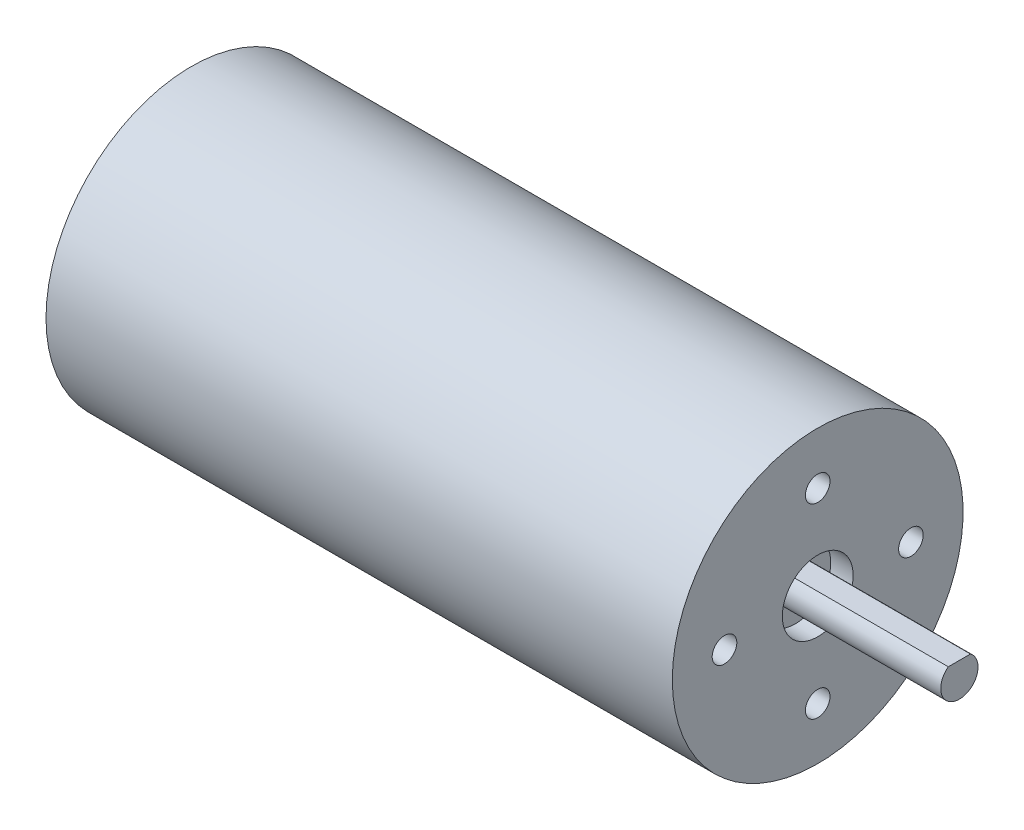
SolidWorks part; units mm, degrees
ref_plane "Front Plane" through (0, 0, 0) normal (0, 0, 1) x (1, 0, 0)
ref_plane "Top Plane" through (0, 0, 0) normal (0, 1, 0) x (1, 0, 0)
ref_plane "Right Plane" through (0, 0, 0) normal (1, 0, 0) x (0, 0, -1)
sketch "Sketch1" plane through (0, 0, 0) normal (1, 0, 0) x (0, 0, -1)
  circle A0 centre (0, 0) radius 19.5
  dimension "D1" = 39
extrude "Boss-Extrude1" add sketch "Sketch1" along normal mid plane 84
sketch "Sketch2" plane through (42, 0, 0) normal (1, 0, 0) x (0, 0, -1)
  circle A0 centre (0, 0) radius 4.75
  dimension "D1" = 9.5
extrude "Cut-Extrude1" cut sketch "Sketch2" against normal blind 3
sketch "Sketch3" plane through (39, 0, 0) normal (1, 0, 0) x (0, 0, -1)
  line L0 (-1.4866, 2.01) -> (1.4866, 2.01)
  arc A0 (-1.4866, 2.01) -> (1.4866, 2.01) centre (0, 0) ccw
  dimension "D1" = 5
  dimension "D2" = 2.01
extrude "Boss-Extrude2" add sketch "Sketch3" along normal blind 22
hole_wizard "Tap Drill for M4x0.7 Tap1" positions "Sketch5" profile "Sketch4" hole size "M4x0.7" standard "ANSI Metric"
sketch "Sketch5" plane through (42, 0, 0) normal (1, 0, 0) x (0, 0, -1)
  line L1 (0, 12.5) -> (0, -12.5) construction
  point P0 (0, 12.5)
  point P11 (12.5, 0)
  point P12 (0, -12.5)
  point P13 (-12.5, 0)
  dimension "D1" = 25
  dimension "D2" = 4
sketch "Sketch4" plane through (42, 12.5, 0) normal (0, 1, 0) x (0, 0, -1)
  line L0 (0, 0) -> (0, 10.9914)
  line L1 (0, 10.9914) -> (1.65, 10)
  line L2 (1.65, 10) -> (1.65, 0)
  line L5 (1.65, 0) -> (0, 0)
  line L10 (0, 10.9914) -> (-1.65, 10) construction
  line L11 (0, -6.35) -> (0, 107.95) construction
  dimension "Hole Dia." = 3.3
  dimension "Hole Depth" = 10
  dimension "Drill Angle" = 118
sketch "Sketch6" plane through (-42, 0, 0) normal (-1, 0, 0) x (0, 0, 1)
  line L0 (0, 0) -> (0, 13.46) construction
  line L1 (-2.185, 13.46) -> (2.185, 13.46) construction
  line L2 (-2.185, 17.03) -> (2.185, 17.03)
  line L3 (-2.185, 9.89) -> (2.185, 9.89)
  arc A0 (-2.185, 17.03) -> (-2.185, 9.89) centre (-2.185, 13.46) ccw
  arc A1 (2.185, 9.89) -> (2.185, 17.03) centre (2.185, 13.46) ccw
  circle A2 centre (0, 0) radius 3.5
  point P5 (0, 13.46)
  dimension "D2" = 3.57
  dimension "D4" = 7
  dimension "D1" = 13.46
  dimension "D3" = 4.37
extrude "Cut-Extrude2" cut sketch "Sketch6" against normal blind 1.33
